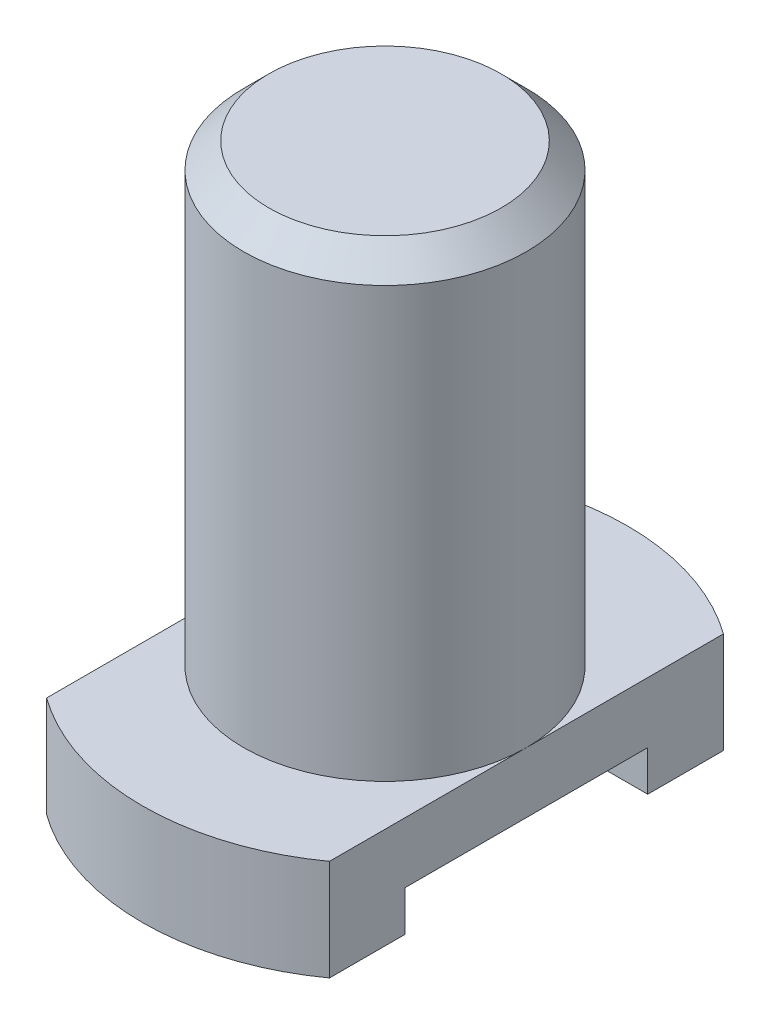
SolidWorks part; units mm, degrees
ref_plane "Front Plane" through (0, 0, 0) normal (0, 0, 1) x (1, 0, 0)
ref_plane "Top Plane" through (0, 0, 0) normal (0, 1, 0) x (1, 0, 0)
ref_plane "Right Plane" through (0, 0, 0) normal (1, 0, 0) x (0, 0, -1)
sketch "Sketch1" plane through (0, 0, 0) normal (0, 1, 0) x (1, 0, 0)
  circle A0 centre (0, 0) radius 1.4
  dimension "D1" = 2.8
extrude "Boss-Extrude3" add sketch "Sketch1" along normal blind 5.5
sketch "Sketch3" plane through (0, 0, 0) normal (0, 1, 0) x (1, 0, 0)
  line L0 (-1.4, -1.9494) -> (-1.4, 1.9494)
  line L1 (1.4, -1.9494) -> (1.4, 1.9494)
  circle A0 centre (0, 0) radius 2.4
  circle A1 centre (0, 0) radius 1.4
  circle A2 centre (0, 0) radius 1.4 construction
  dimension "D1" = 0
  dimension "D2" = 1
extrude "Boss-Extrude4" add sketch "Sketch3" along normal blind 1 contours L1 A0 L0
chamfer "Chamfer1" distance 0.25 angle 45 1 edges at (0, 5.5, 1.4)
sketch "Sketch4" plane through (1.4, 0, 0) normal (1, 0, 0) x (0, 0, -1)
  line L1 (-1.2, -0.4) -> (1.2, -0.4)
  line L2 (-1.2, -0.4) -> (-1.2, 0.4)
  line L3 (-1.2, 0.4) -> (1.2, 0.4)
  line L4 (1.2, -0.4) -> (1.2, 0.4)
  line L5 (-1.2, -0.4) -> (1.2, 0.4) construction
  line L6 (-1.2, 0.4) -> (1.2, -0.4) construction
  point P0 (0, 0)
  dimension "D1" = 2.4
  dimension "D2" = 0.8
extrude "Cut-Extrude1" cut sketch "Sketch4" against normal blind 3.6
